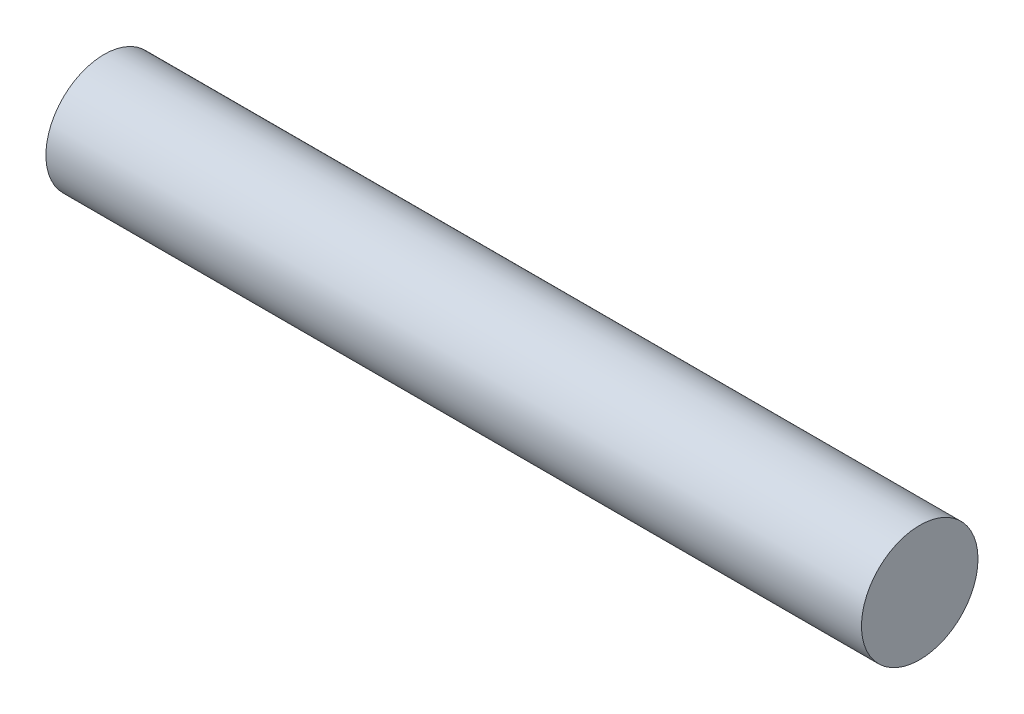
SolidWorks part; units mm, degrees
material "Alloy Steel"
ref_plane "Front Plane" through (0, 0, 0) normal (0, 0, 1) x (1, 0, 0)
ref_plane "Top Plane" through (0, 0, 0) normal (0, 1, 0) x (1, 0, 0)
ref_plane "Right Plane" through (0, 0, 0) normal (1, 0, 0) x (0, 0, -1)
sketch "Sketch1" plane through (0, 0, 0) normal (1, 0, 0) x (0, 0, -1)
  circle A0 centre (0, 0) radius 6.35
  dimension "D1" = 12.7
extrude "Boss-Extrude1" add sketch "Sketch1" along normal mid plane 88.9
